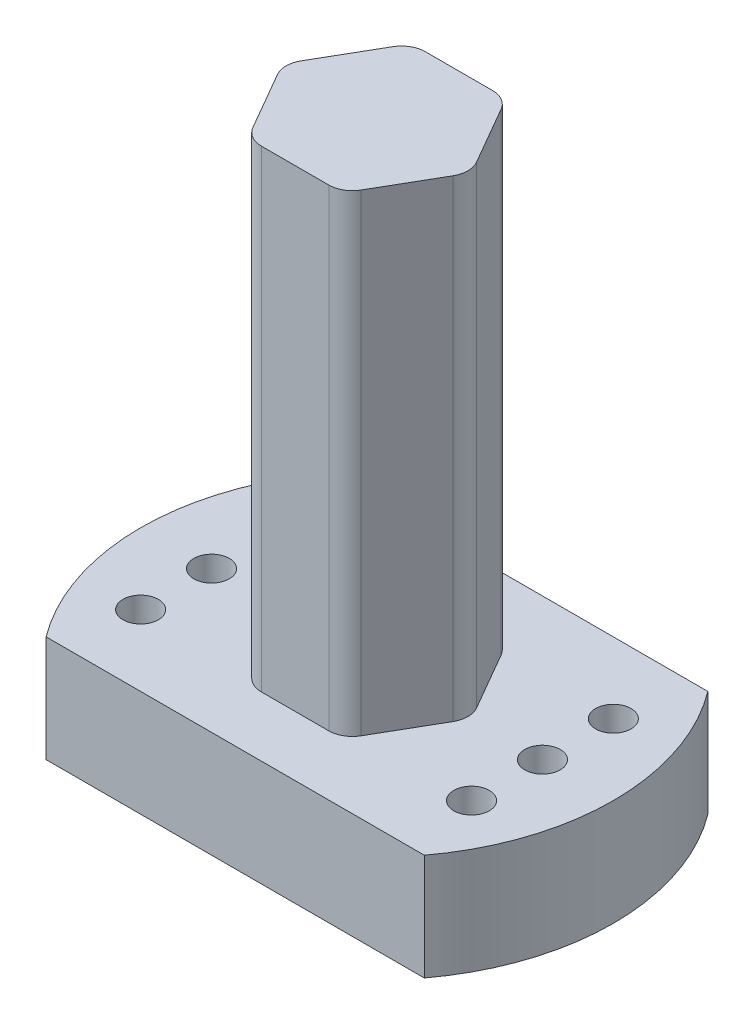
SolidWorks part; units mm, degrees
ref_plane "Спереди" through (0, 0, 0) normal (0, 0, 1) x (1, 0, 0)
ref_plane "Сверху" through (0, 0, 0) normal (0, 1, 0) x (1, 0, 0)
ref_plane "Справа" through (0, 0, 0) normal (1, 0, 0) x (0, 0, -1)
sketch "Эскиз1" plane through (0, 0, 0) normal (0, 1, 0) x (1, 0, 0)
  line L0 (0, -1000) -> (0, 49000) construction
  line L1 (-8, 6) -> (8, 6)
  line L3 (8, -6) -> (-8, -6)
  arc A0 (-8, 6) -> (-8, -6) centre (0, 0) ccw
  circle A12 centre (-7, 3) radius 0.75
  arc A14 (8, -6) -> (8, 6) centre (0, 0) ccw
  circle A15 centre (-7, 0) radius 0.75
  circle A16 centre (-7, -3) radius 0.75
  circle A17 centre (7, -3) radius 0.75
  circle A18 centre (7, 0) radius 0.75
  circle A19 centre (7, 3) radius 0.75
  point P29 (0, 0)
  dimension "D1" = 10
  dimension "D4" = 1.5
  dimension "D2" = 7
  dimension "D3" = 3
  dimension "D5" = 12
  dimension "D7" = 3
  dimension "D6" = 3
extrude "Бобышка-Вытянуть1" add sketch "Эскиз1" along normal blind 4.5
sketch "Эскиз2" plane through (0, 4.5, 0) normal (0, 1, 0) x (1, 0, 0)
  line L1 (2, 3.4641) -> (-2, 3.4641)
  line L2 (-2, 3.4641) -> (-4, 0)
  line L3 (-4, 0) -> (-2, -3.4641)
  line L4 (-2, -3.4641) -> (2, -3.4641)
  line L5 (2, -3.4641) -> (4, 0)
  line L6 (4, 0) -> (2, 3.4641)
  circle A0 centre (0, 0) radius 3.4641 construction
  dimension "D1" = 8
extrude "Бобышка-Вытянуть2" add sketch "Эскиз2" along normal blind 20
fillet "Скругление1" radius 1 6 edges at (-4, 14.5, 0) (-2, 14.5, -3.4641) (2, 14.5, -3.4641) (4, 14.5, 0) (2, 14.5, 3.4641) (-2, 14.5, 3.4641)
